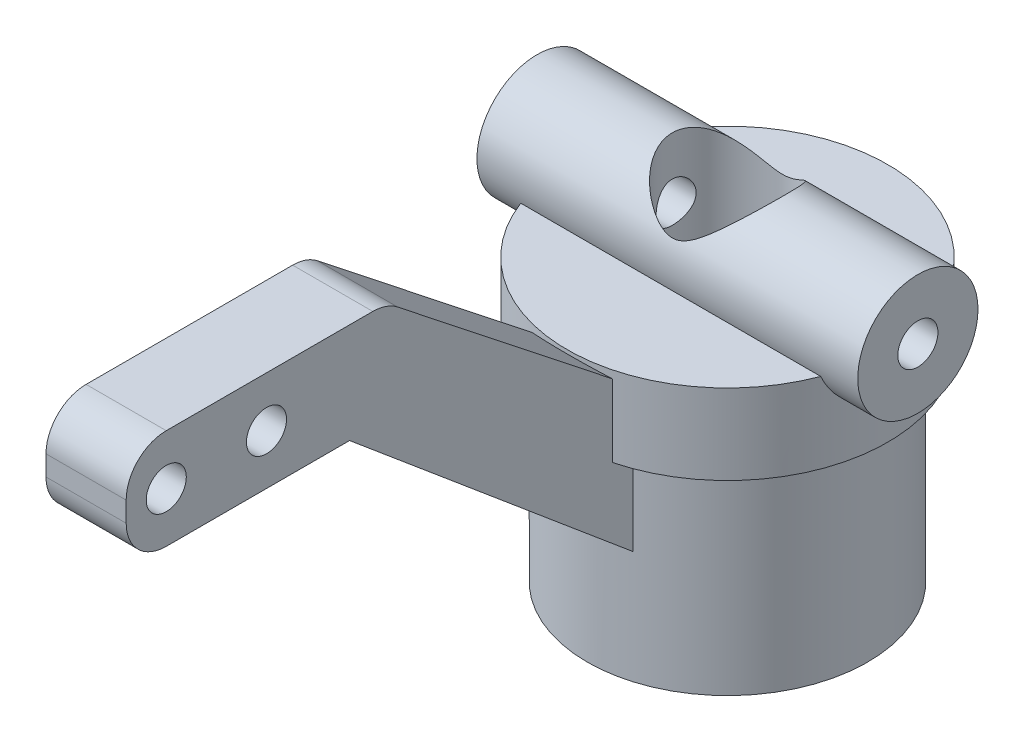
SolidWorks part; units mm, degrees
ref_plane "前视基准面" through (0, 0, 0) normal (0, 0, 1) x (1, 0, 0)
ref_plane "上视基准面" through (0, 0, 0) normal (0, 1, 0) x (1, 0, 0)
ref_plane "右视基准面" through (0, 0, 0) normal (1, 0, 0) x (0, 0, -1)
sketch "草图1" plane through (0, 0, 0) normal (0, 1, 0) x (1, 0, 0)
  circle A0 centre (0, 0) radius 7
  dimension "D1" = 14
extrude "凸台-拉伸1" add sketch "草图1" along normal blind 10
sketch "草图2" plane through (0, 10, 0) normal (0, 1, 0) x (1, 0, 0)
  circle A0 centre (0, 0) radius 8
  dimension "D1" = 16
extrude "凸台-拉伸2" add sketch "草图2" along normal blind 4
sketch "草图3" plane through (0, 0, 0) normal (1, 0, 0) x (0, 0, -1)
  circle A0 centre (0, 15) radius 3
  dimension "D1" = 6
  dimension "D2" = 15
extrude "凸台-拉伸3" add sketch "草图3" along normal mid plane 19
sketch "草图4" plane through (9.5, 0, 0) normal (1, 0, 0) x (0, 0, -1)
  circle A0 centre (0, 15) radius 1
  dimension "D1" = 2
extrude "切除-拉伸1" cut sketch "草图4" against normal through all both and the other way through all
sketch "草图8" plane through (0, 0, 0) normal (1, 0, 0) x (0, 0, -1)
  line L0 (0, 0) -> (0, 15) construction
  line L1 (0, 0) -> (-20.8557, 17.5)
  line L2 (-20.8557, 17.5) -> (-32, 17.5)
  line L3 (-32, 17.5) -> (-32, 22.5)
  line L4 (-32, 22.5) -> (-19, 22.5)
  line L5 (-19, 22.5) -> (0, 7.5)
  line L6 (0, 7.5) -> (0, 0)
  line L7 (-18.9979, 20) -> (-32, 20) construction
  circle A1 centre (-30, 20) radius 1
  circle A2 centre (-25, 20) radius 1
  point P13 (-19, 17.5)
  dimension "D8" = 2
  dimension "D1" = 50
  dimension "D2" = 5
  dimension "D4" = 32
  dimension "D5" = 13
  dimension "D6" = 30
  dimension "D7" = 5
  dimension "D9" = 5
extrude "凸台-拉伸4" add sketch "草图8" along normal mid plane 4
hole_wizard "M5 六角头螺栓的柱形沉头孔1" positions "草图5" profile "草图7" counterbore size "M5" standard "GB" end condition through all
sketch "草图5" plane through (0, 0, 0) normal (0, -1, 0) x (-1, 0, 0)
  point P0 (0, 0)
sketch "草图7" plane through (0, 0, 0) normal (1, 0, 0) x (0, 0, -1)
  line L0 (0, 0) -> (0, 22.5)
  line L1 (0, 22.5) -> (2.75, 22.5)
  line L3 (2.75, 22.5) -> (2.75, 6.5)
  line L4 (2.75, 6.5) -> (5.5, 6.5)
  line L5 (5.5, 6.5) -> (5.5, 0)
  line L7 (5.5, 0) -> (0, 0)
  line L11 (0, -6.35) -> (0, 107.95) construction
  dimension "通孔孔直径" = 5.5
  dimension "通孔孔深度" = 22.5
  dimension "柱形沉头孔直径" = 11
  dimension "柱形沉头孔深度" = 6.5
fillet "圆角1" radius 2 3 edges at (0, 22.5, 19) (0, 22.5, 32) (0, 17.5, 32)
